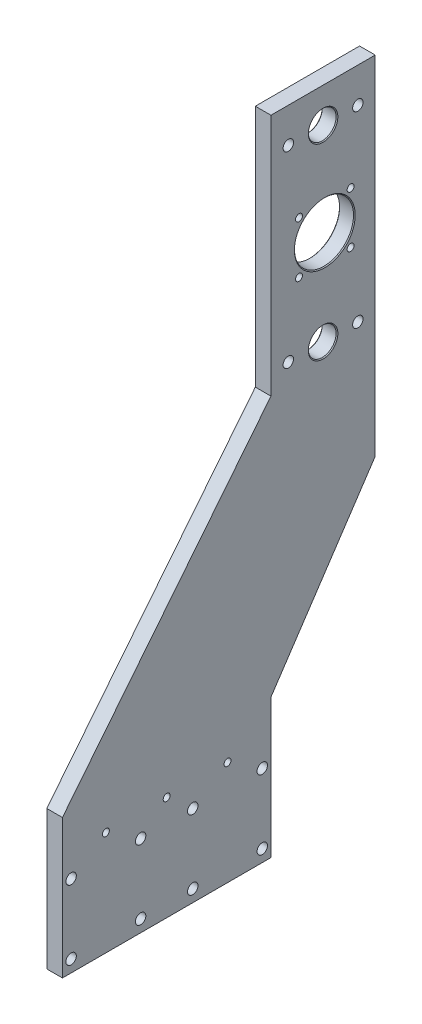
SolidWorks part; units mm, degrees
ref_plane "Alzado" through (0, 0, 0) normal (0, 0, 1) x (1, 0, 0)
ref_plane "Planta" through (0, 0, 0) normal (0, 1, 0) x (1, 0, 0)
ref_plane "Vista lateral" through (0, 0, 0) normal (1, 0, 0) x (0, 0, -1)
sketch "Croquis1" plane through (0, 0, 0) normal (1, 0, 0) x (0, 0, -1)
  line L0 (-294.7966, -440.4595) -> (-174.7966, -290.4595)
  line L1 (-174.7966, -150.4595) -> (-114.7966, -150.4595)
  line L2 (-174.7966, -150.4595) -> (-174.7966, -290.4595)
  line L3 (-294.7966, -440.4595) -> (-294.7966, -520.4595)
  line L4 (-114.7966, -150.4595) -> (-114.7966, -350.4595)
  line L5 (-174.7966, -440.4595) -> (-174.7966, -520.4595)
  line L6 (-294.7966, -520.4595) -> (-174.7966, -520.4595)
  line L7 (-114.7966, -350.4595) -> (-174.7966, -440.4595)
  point P0 (-82.2625, -137.8814)
  dimension "D1" = 60
  dimension "D2" = 200
  dimension "D3" = 80
  dimension "D4" = 120
  dimension "D5" = 80
  dimension "D6" = 60
  dimension "D7" = 370
  dimension "D8" = 140
  dimension "D9" = 120
extrude "Saliente-Extruir1" add sketch "Croquis1" along normal mid plane 9
sketch "Croquis4" plane through (4.5, 0, 0) normal (1, 0, 0) x (0, 0, -1)
  line L0 (-174.7966, -350.4595) -> (-114.7966, -350.4595) construction
  line L1 (-174.7966, -150.4595) -> (-174.7966, -350.4595) construction
  line L2 (-143.7966, -155.5439) -> (-143.7966, -234.3166) construction
  line L3 (-114.7966, -150.4595) -> (-174.7966, -150.4595) construction
  line L4 (-158.6459, -209.6102) -> (-158.6459, -239.3087) construction
  circle A0 centre (-143.7966, -224.4595) radius 17
  circle A1 centre (-158.6459, -209.6102) radius 2
  circle A2 centre (-128.9474, -209.6102) radius 2
  circle A3 centre (-128.9474, -239.3087) radius 2
  circle A4 centre (-158.6459, -239.3087) radius 2
  point P22 (-143.7966, -224.4595)
  dimension "D1" = 74
  dimension "D2" = 4
  dimension "D3" = 4
  dimension "D4" = 21
  dimension "D5" = 21
  dimension "D6" = 21
  dimension "D7" = 21
  dimension "D8" = 21
  dimension "D10" = 34
  dimension "D9" = 31
extrude "Cortar-Extruir3" cut sketch "Croquis4" against normal through all
chamfer "Chaflán1" distance 0.5 angle 45 6 edges at (-4.5, -239.3087, 156.6459) (-4.5, -209.6102, 156.6459) (-4.5, -239.3087, 126.9474) (-4.5, -209.6102, 126.9474) (4.5, -224.4595, 126.7966) (-4.5, -224.4595, 126.7966)
sketch "Croquis5" plane through (4.5, 0, 0) normal (1, 0, 0) x (0, 0, -1)
  line L0 (-174.7966, -350.4595) -> (-174.7966, -150.4595) construction
  line L1 (-114.7966, -350.4595) -> (-174.7966, -350.4595) construction
  line L2 (-144.7966, -150.4595) -> (-144.7966, -350.4595) construction
  line L3 (-114.7966, -150.4595) -> (-174.7966, -150.4595) construction
  line L4 (-114.7966, -170.4595) -> (-174.7966, -170.4595) construction
  line L5 (-114.7966, -350.4595) -> (-114.7966, -150.4595) construction
  line L6 (-134.7966, -278.4595) -> (-194.7966, -278.4595) construction
  line L7 (-164.7966, -170.4595) -> (-164.7966, -278.4595) construction
  line L8 (-124.7966, -170.4595) -> (-124.7966, -278.4595) construction
  circle A0 centre (-144.7966, -170.4595) radius 8
  circle A1 centre (-144.7966, -278.4595) radius 8
  circle A2 centre (-124.7966, -170.4595) radius 3
  circle A3 centre (-164.7966, -170.4595) radius 3
  circle A4 centre (-164.7966, -278.4595) radius 3
  circle A5 centre (-124.7966, -278.4595) radius 3
  dimension "D1" = 16
  dimension "D2" = 16
  dimension "D3" = 20
  dimension "D4" = 108
  dimension "D5" = 6
  dimension "D6" = 20
  dimension "D7" = 20
extrude "Cortar-Extruir4" cut sketch "Croquis5" against normal through all
chamfer "Chaflán2" distance 0.5 angle 45 8 edges at (-4.5, -278.4595, 161.7966) (4.5, -278.4595, 136.7966) (-4.5, -278.4595, 136.7966) (-4.5, -278.4595, 121.7966) (-4.5, -170.4595, 161.7966) (4.5, -170.4595, 136.7966) (-4.5, -170.4595, 136.7966) (-4.5, -170.4595, 121.7966)
sketch "Croquis3" plane through (4.5, 0, 0) normal (1, 0, 0) x (0, 0, -1)
  line L0 (-294.7966, -466.4595) -> (-174.7966, -466.4595) construction
  line L1 (-294.7966, -440.4595) -> (-294.7966, -520.4595) construction
  line L2 (-174.7966, -520.4595) -> (-174.7966, -440.4595) construction
  line L3 (-294.7966, -520.4595) -> (-174.7966, -520.4595) construction
  line L4 (-234.7966, -466.4595) -> (-234.7966, -520.4595) construction
  line L5 (-289.7966, -473.4595) -> (-289.7966, -513.4595) construction
  line L6 (-289.7966, -513.4595) -> (-249.7966, -513.4595) construction
  line L7 (-249.7966, -513.4595) -> (-249.7966, -473.4595) construction
  line L8 (-249.7966, -473.4595) -> (-289.7966, -473.4595) construction
  circle A0 centre (-289.7966, -473.4595) radius 3
  circle A1 centre (-289.7966, -513.4595) radius 3
  circle A2 centre (-249.7966, -473.4595) radius 3
  circle A3 centre (-249.7966, -513.4595) radius 3
  circle A4 centre (-219.7966, -513.4595) radius 3
  circle A5 centre (-219.7966, -473.4595) radius 3
  circle A6 centre (-179.7966, -513.4595) radius 3
  circle A7 centre (-179.7966, -473.4595) radius 3
  dimension "D6" = 6
  dimension "D7" = 54
  dimension "D1" = 40
  dimension "D2" = 40
  dimension "D3" = 5
  dimension "D4" = 7
  dimension "D5" = 7
extrude "Cortar-Extruir2" cut sketch "Croquis3" against normal through all
chamfer "Chaflán3" distance 0.5 angle 45 8 edges at (-4.5, -513.4595, 286.7966) (-4.5, -473.4595, 286.7966) (-4.5, -513.4595, 246.7966) (-4.5, -473.4595, 246.7966) (-4.5, -513.4595, 222.7966) (-4.5, -473.4595, 222.7966) (-4.5, -513.4595, 182.7966) (-4.5, -473.4595, 182.7966)
sketch "Croquis2" plane through (4.5, 0, 0) normal (1, 0, 0) x (0, 0, -1)
  line L0 (-294.7966, -460.4595) -> (-174.7966, -460.4595) construction
  line L1 (-294.7966, -440.4595) -> (-294.7966, -520.4595) construction
  line L2 (-174.7966, -520.4595) -> (-174.7966, -440.4595) construction
  line L3 (-294.7966, -520.4595) -> (-174.7966, -520.4595) construction
  circle A0 centre (-234.7966, -460.4595) radius 2
  circle A1 centre (-269.7966, -460.4595) radius 2
  circle A2 centre (-199.7966, -460.4595) radius 2
  dimension "D2" = 4
  dimension "D3" = 35
  dimension "D4" = 35
  dimension "D1" = 60
extrude "Cortar-Extruir1" cut sketch "Croquis2" against normal through all
chamfer "Chaflán4" distance 0.5 angle 45 3 edges at (-4.5, -460.4595, 267.7966) (-4.5, -460.4595, 232.7966) (-4.5, -460.4595, 197.7966)
